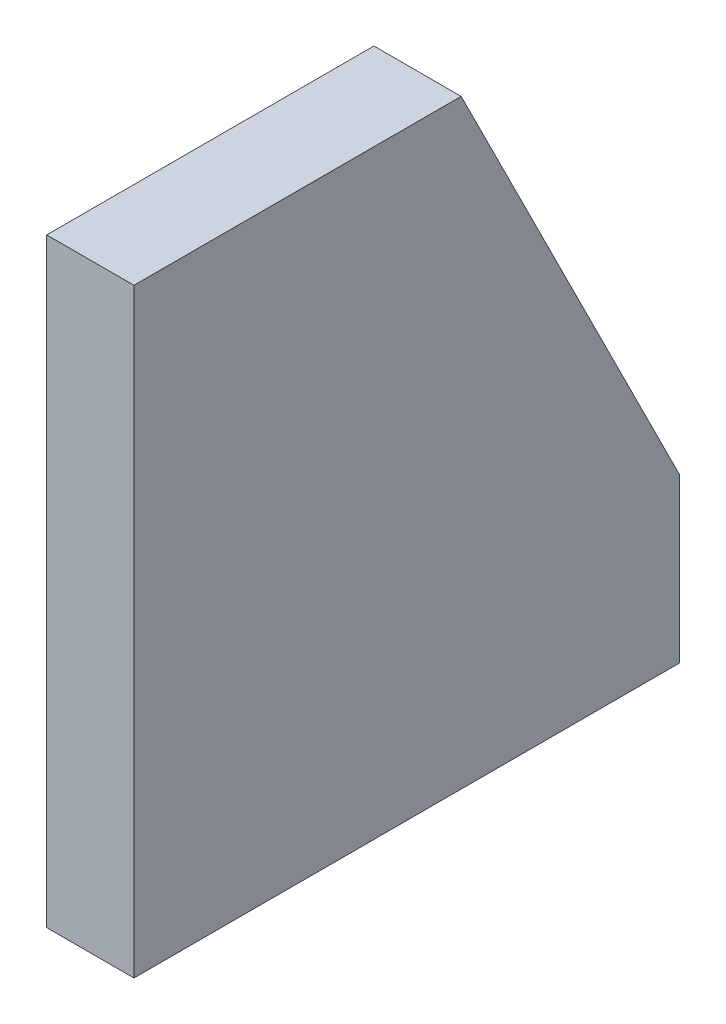
SolidWorks part; units mm, degrees
material "ASTM A36 Steel"
ref_plane "Front Plane" through (0, 0, 0) normal (0, 0, 1) x (1, 0, 0)
ref_plane "Top Plane" through (0, 0, 0) normal (0, 1, 0) x (1, 0, 0)
ref_plane "Right Plane" through (0, 0, 0) normal (1, 0, 0) x (0, 0, -1)
sketch "Sketch1" plane through (0, 0, 0) normal (1, 0, 0) x (0, 0, -1)
  line L0 (6.1688, -11.3636) -> (-43.8312, -11.3636)
  line L1 (-43.8312, -11.3636) -> (-43.8312, 43.6364)
  line L2 (-43.8312, 43.6364) -> (-13.8312, 43.6364)
  line L3 (-13.8312, 43.6364) -> (6.1688, 3.6364)
  line L4 (6.1688, 3.6364) -> (6.1688, -11.3636)
  dimension "D1" = 50
  dimension "D2" = 55
  dimension "D3" = 15
  dimension "D4" = 30
extrude "Boss-Extrude1" add sketch "Sketch1" along normal blind 8
